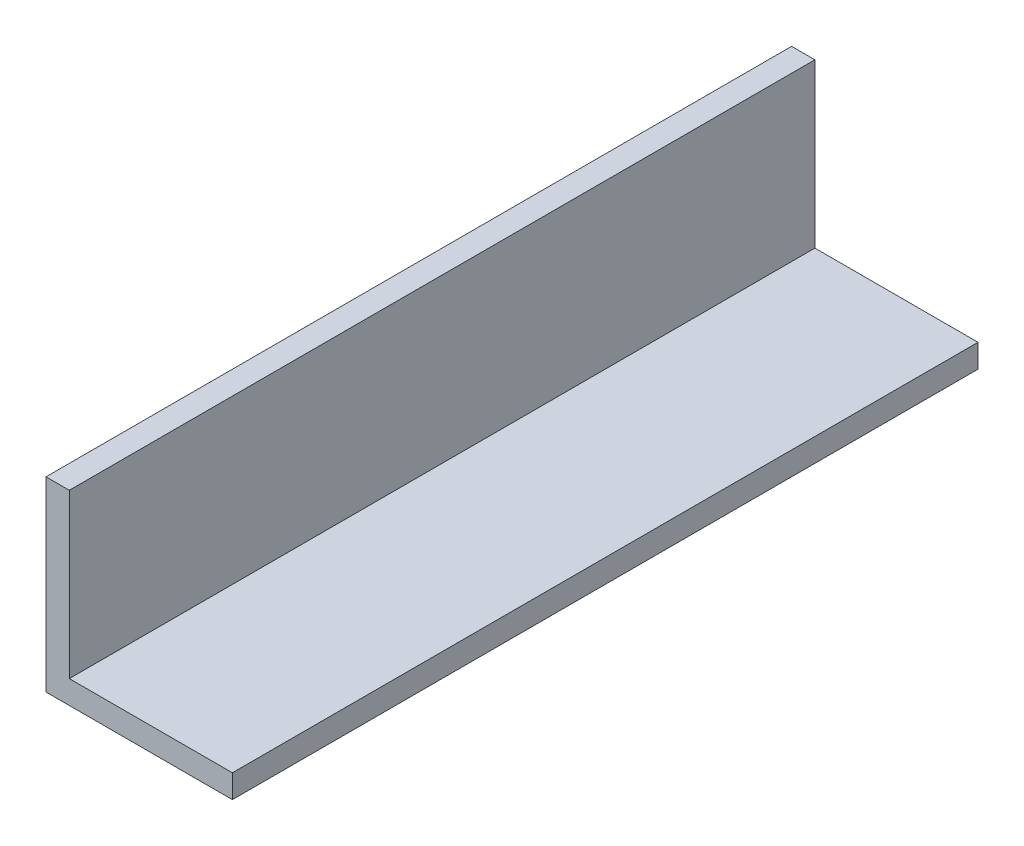
SolidWorks part; units mm, degrees
ref_plane "Спереди" through (0, 0, 0) normal (0, 0, 1) x (1, 0, 0)
ref_plane "Сверху" through (0, 0, 0) normal (0, 1, 0) x (1, 0, 0)
ref_plane "Справа" through (0, 0, 0) normal (1, 0, 0) x (0, 0, -1)
sketch "Эскиз1" plane through (0, 0, 0) normal (0, 0, 1) x (1, 0, 0)
  line L0 (0, 4.7944) -> (0, -30.2056)
  line L1 (0, -30.2056) -> (35, -30.2056)
  line L2 (35, -30.2056) -> (35, -35.2056)
  line L3 (35, -35.2056) -> (-5, -35.2056)
  line L4 (-5, -35.2056) -> (-5, 4.7944)
  line L5 (-5, 4.7944) -> (0, 4.7944)
extrude "Вытянуть1" add sketch "Эскиз1" along normal blind 160
